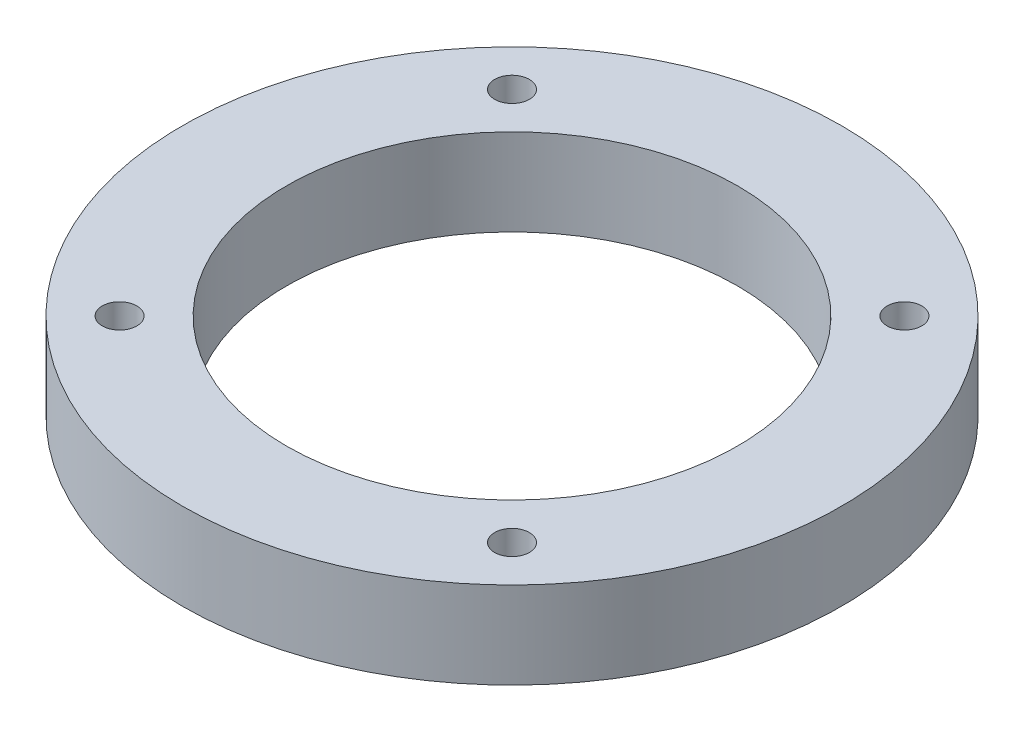
SolidWorks part; units mm, degrees
material "6061 Alloy"
ref_plane "Front Plane" through (0, 0, 0) normal (0, 0, 1) x (1, 0, 0)
ref_plane "Top Plane" through (0, 0, 0) normal (0, 1, 0) x (1, 0, 0)
ref_plane "Right Plane" through (0, 0, 0) normal (1, 0, 0) x (0, 0, -1)
sketch "Sketch1" plane through (0, 0, 0) normal (0, 1, 0) x (1, 0, 0)
  circle A0 centre (0, 0) radius 26
  circle A1 centre (0, 0) radius 38
  circle A2 centre (-22.625, 22.625) radius 2
  circle A3 centre (22.625, 22.625) radius 2
  circle A4 centre (22.625, -22.625) radius 2
  circle A5 centre (-22.625, -22.625) radius 2
  point P15 (0, 0)
  dimension "D1" = 76
  dimension "D2" = 12
  dimension "D4" = 45.25
  dimension "D5" = 4
  dimension "D3" = 4
extrude "Boss-Extrude1" add sketch "Sketch1" along normal blind 10
